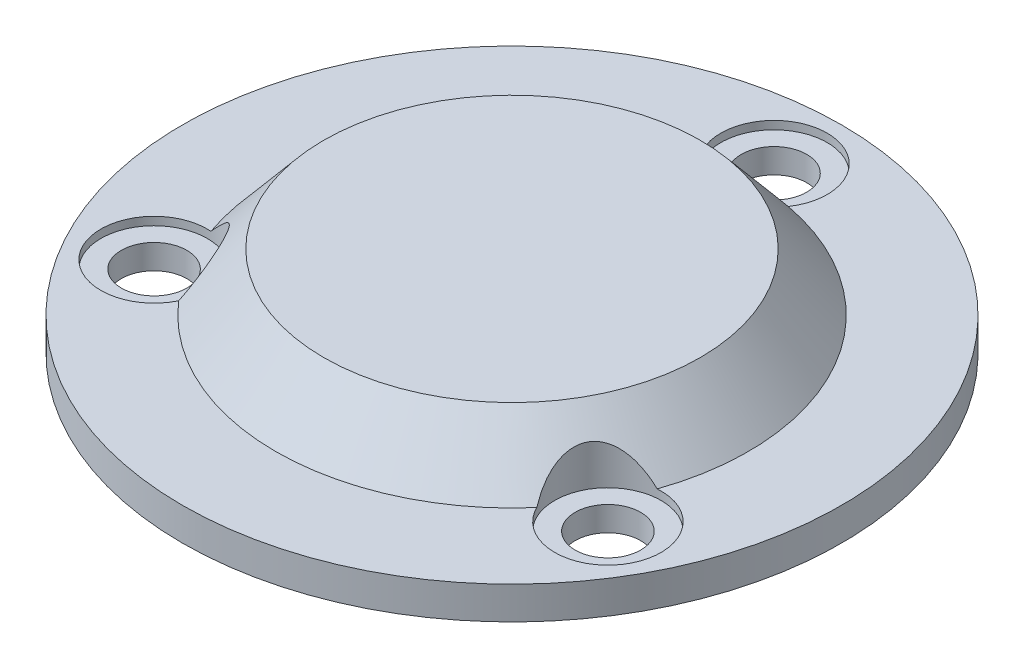
SolidWorks part; units mm, degrees
ref_plane "Front Plane" through (0, 0, 0) normal (0, 0, 1) x (1, 0, 0)
ref_plane "Top Plane" through (0, 0, 0) normal (0, 1, 0) x (1, 0, 0)
ref_plane "Right Plane" through (0, 0, 0) normal (1, 0, 0) x (0, 0, -1)
sketch "Sketch1" plane through (0, 0, 0) normal (0, 0, 1) x (1, 0, 0)
  line L0 (0, 0) -> (0, 4)
  line L1 (0, 4) -> (-22.9915, 4)
  line L2 (-22.9915, 4) -> (-28.8652, -3)
  line L3 (-28.8652, -3) -> (-40.25, -3)
  line L4 (-40.25, -3) -> (-40.25, -7)
  line L5 (-40.25, -7) -> (-27, -7)
  line L6 (-27, -7) -> (-21.1263, 0)
  line L7 (-21.1263, 0) -> (0, 0)
  line L8 (0, 4) -> (0, 0) construction
  dimension "D1" = 27
  dimension "D2" = 4
  dimension "D3" = 4
  dimension "D4" = 4
  dimension "D5" = 40.25
  dimension "D6" = 7
  dimension "D7" = 130
revolve "Revolve1" add sketch "Sketch1" angle 360 about L8
sketch "Sketch2" plane through (0, -3, 0) normal (0, 1, 0) x (1, 0, 0)
  circle A0 centre (0, 32) radius 4
  circle A1 centre (27.7128, -16) radius 4
  circle A2 centre (-27.7128, -16) radius 4
  point P10 (0, 0)
  dimension "D2" = 8
  dimension "D1" = 32
  dimension "D3" = 3
extrude "Cut-Extrude1" cut sketch "Sketch2" against normal through all
sketch "Sketch3" plane through (0, -3, 0) normal (0, 1, 0) x (1, 0, 0)
  circle A0 centre (0, 32) radius 6.5
  circle A1 centre (27.7128, -16) radius 6.5
  circle A2 centre (-27.7128, -16) radius 6.5
  dimension "D1" = 13
  dimension "D2" = 13
  dimension "D3" = 13
extrude "Cut-Extrude2" cut sketch "Sketch3" against normal blind 1 and the other way through all
